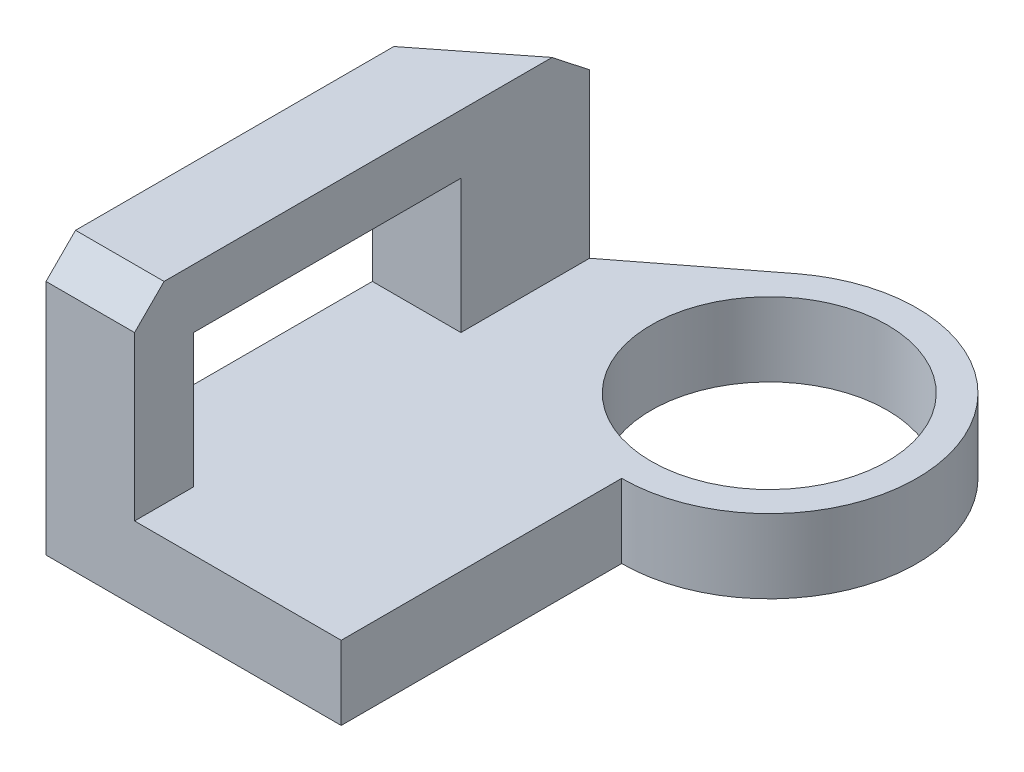
SolidWorks part; units mm, degrees
material "ABS"
ref_plane "Front Plane" through (0, 0, 0) normal (0, 0, 1) x (1, 0, 0)
ref_plane "Top Plane" through (0, 0, 0) normal (0, 1, 0) x (1, 0, 0)
ref_plane "Right Plane" through (0, 0, 0) normal (1, 0, 0) x (0, 0, -1)
sketch "Sketch1" plane through (0, 0, 0) normal (0, 1, 0) x (1, 0, 0)
  line L14 (0, -12.7) -> (0, -36.83)
  line L20 (-25.4, -36.83) -> (-25.4, -17.78)
  line L22 (-25.4, -17.3267) -> (-25.4, -17.78)
  line L23 (-25.4, -36.83) -> (0, -36.83)
  line L24 (-25.4, -3.556) -> (-25.4, -17.3267)
  line L25 (-25.4, -3.556) -> (-7.7577, 10.0552)
  arc A0 (-10.0491, -1.4969) -> (-9.9857, 1.8737) centre (0, 0) ccw
  arc A3 (0, -12.7) -> (-7.7577, 10.0552) centre (0, 0) ccw
  arc A4 (-10.0491, -1.4969) -> (-9.9857, 1.8737) centre (0, 0) ccw
  arc A5 (0, -12.7) -> (-7.7577, 10.0552) centre (0, 0) ccw
  circle A7 centre (0, 0) radius 10.16
  dimension "D1" = 20.32
  dimension "D2" = 25.4
  dimension "D4" = 12.7
  dimension "D3" = 36.83
  dimension "D5" = 33.274
extrude "Boss-Extrude1" add sketch "Sketch1" along normal blind 6.35
sketch "Sketch6" plane through (0, 6.35, 0) normal (0, 1, 0) x (1, 0, 0)
  line L0 (-17.78, -3.67) -> (-17.78, 2.3229)
  line L1 (-17.78, -31.75) -> (-25.4, -31.75)
  line L2 (-17.78, -31.75) -> (-17.78, -36.83)
  line L3 (-17.78, -36.83) -> (-25.4, -36.83)
  line L4 (-25.4, -31.75) -> (-25.4, -36.83)
  line L5 (-25.4, -3.556) -> (-25.4, -36.83) construction
  line L6 (-25.4, -36.83) -> (0, -36.83) construction
  line L7 (-25.4, -3.556) -> (-7.7577, 10.0552) construction
  line L8 (-25.4, -3.67) -> (-17.78, -3.67)
  line L9 (-25.4, -3.67) -> (-25.4, -8.75)
  line L10 (-25.4, -8.75) -> (-17.78, -8.75)
  line L11 (-17.78, -3.67) -> (-17.78, -8.75)
  line L12 (-17.78, 2.3229) -> (-25.4, -3.67)
  line M13 (-25.4, -3.556) -> (-25.4, -36.83)
  line M14 (-25.4, -36.83) -> (0, -36.83)
  dimension "D1" = 5.08
  dimension "D2" = 7.62
  dimension "D3" = 23
extrude "Boss-Extrude3" add sketch "Sketch6" along normal blind 16.58 contours L0 L12 L8 | L11 L8 L10 M13 | L2 L1 M13 M14
sketch "Sketch8" plane through (0, 0, 8.75) normal (0, 0, 1) x (1, 0, 0)
  line L0 (-17.78, 22.93) -> (-17.78, 6.35) construction
  line L1 (-25.4, 22.93) -> (-17.78, 22.93)
  line L2 (-25.4, 22.93) -> (-25.4, 17.85)
  line L3 (-25.4, 17.85) -> (-17.78, 17.85)
  line L4 (-17.78, 22.93) -> (-17.78, 17.85)
  line L5 (-25.4, 22.93) -> (-17.78, 22.93) construction
  dimension "D1" = 5.08
extrude "Boss-Extrude4" add sketch "Sketch8" along normal up to surface (23 mm away) up to face at (-21.59, 14.64, 31.75)
chamfer "Chamfer1" distance 2.54 angle 45 2 edges at (-21.59, 22.93, 0.6735) (-21.59, 22.93, 36.83)
